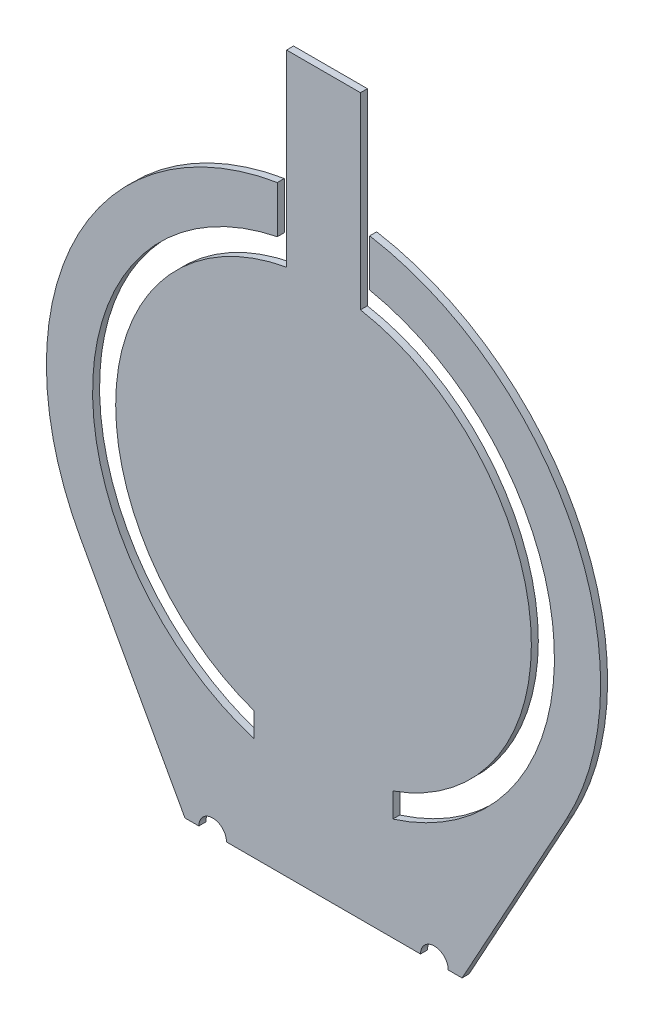
SolidWorks part; units mm, degrees
ref_plane "Plano frontal" through (0, 0, 0) normal (0, 0, 1) x (1, 0, 0)
ref_plane "Plano superior" through (0, 0, 0) normal (0, 1, 0) x (1, 0, 0)
ref_plane "Plano direito" through (0, 0, 0) normal (1, 0, 0) x (0, 0, -1)
sketch "Sketch1" plane through (0, 0, 0) normal (0, 0, 1) x (1, 0, 0)
  line L1 (-15, -35) -> (15, -35)
  line L4 (-15, -35) -> (-7.5, -35)
  line L7 (15, -35) -> (26.2929, -14.4459)
  line L9 (-7.5, -23.8485) -> (-7.5, -21.2132)
  line L12 (7.5, -23.8485) -> (7.5, -21.2132)
  line L16 (-15, -35) -> (-26.2929, -14.4459)
  line L17 (-15, -35) -> (-5, -35)
  arc A0 (7.5, -21.2132) -> (-7.5, -21.2132) centre (0, 0) ccw
  arc A1 (7.5, -23.8485) -> (-7.5, -23.8485) centre (0, 0) ccw
  arc A2 (26.2929, -14.4459) -> (-26.2929, -14.4459) centre (0, 0) ccw
  point P10 (0, -35)
  dimension "D1" = 45
  dimension "D2" = 50
  dimension "D3" = 60
  dimension "D5" = 30
  dimension "D8" = 2.6353
extrude "Boss-Extrude1" add sketch "Sketch1" along normal blind 0.7544
sketch "Esboço1" plane through (0, 0, 0.7544) normal (0, 0, 1) x (1, 0, 0)
  line L0 (0, 30) -> (0, 25)
  line L1 (-5, 27.5) -> (5, 27.5)
  line L3 (-5, 24.0986) -> (5, 24.0986)
  line L4 (-5, 24.0986) -> (-5, 30.9014)
  line L5 (-5, 30.9014) -> (5, 30.9014)
  line L6 (5, 24.0986) -> (5, 30.9014)
  line L7 (-5, 24.0986) -> (5, 30.9014) construction
  line L8 (-5, 30.9014) -> (5, 24.0986) construction
  arc A2 (26.2929, -14.4459) -> (-26.2929, -14.4459) centre (0, 0) ccw construction
  arc A3 (7.5, -23.8485) -> (-7.5, -23.8485) centre (0, 0) ccw construction
  point P8 (0, 27.5)
  point P11 (0, 27.5)
  arc M6 (-7.5, -23.8485) -> (7.5, -23.8485) centre (0, 0) cw
  arc M11 (26.2929, -14.4459) -> (-26.2929, -14.4459) centre (0, 0) ccw
  dimension "D1" = 10
extrude "Corte-extrusão1" cut sketch "Esboço1" against normal blind 10 contours L6 L5 L4 M11 | L4 L1 L0 M11 | L1 L6 L0 M11 | L6 L1 L0 M6 | L4 L0 L1 M6 | L3 L6 L4 M6
sketch "Esboço3" plane through (0, 0, 0.7544) normal (0, 0, 1) x (1, 0, 0)
  line L0 (0, 22.5) -> (0, 42.5)
  line L1 (0, 22.5) -> (0, 20.9256)
  line L3 (-5, 24.4949) -> (-4, 24.4949)
  line L4 (-4, 20.9256) -> (4, 20.9256)
  line L5 (-4, 20.9256) -> (-4, 42.5)
  line L6 (4, 20.9256) -> (4, 42.5)
  line L7 (4, 42.5) -> (-4, 42.5)
  arc A2 (7.5, -21.2132) -> (-7.5, -21.2132) centre (0, 0) ccw construction
  arc M14 (7.5, -21.2132) -> (-7.5, -21.2132) centre (0, 0) ccw
  dimension "D1" = 20
  dimension "D2" = 1
  dimension "D3" = 8
extrude "Ressalto-extrusão1" add sketch "Esboço3" against normal blind 0.7544 contours L0 L7 L5 M14 | L6 L7 L0 M14
sketch "Esboço4" plane through (0, 0, 0.7544) normal (0, 0, 1) x (1, 0, 0)
  line L0 (-15, -35) -> (-12, -35)
  line L1 (-15, -35) -> (15, -35) construction
  line L2 (0, -35) -> (0, -27.9219)
  circle A0 centre (-12, -35) radius 1.5
  circle A1 centre (12, -35) radius 1.5
  line M8 (-15, -35) -> (15, -35)
  dimension "D2" = 3
  dimension "D1" = 3
extrude "Corte-extrusão2" cut sketch "Esboço4" against normal blind 10 contours A0 L0 M8 | A1 M8
